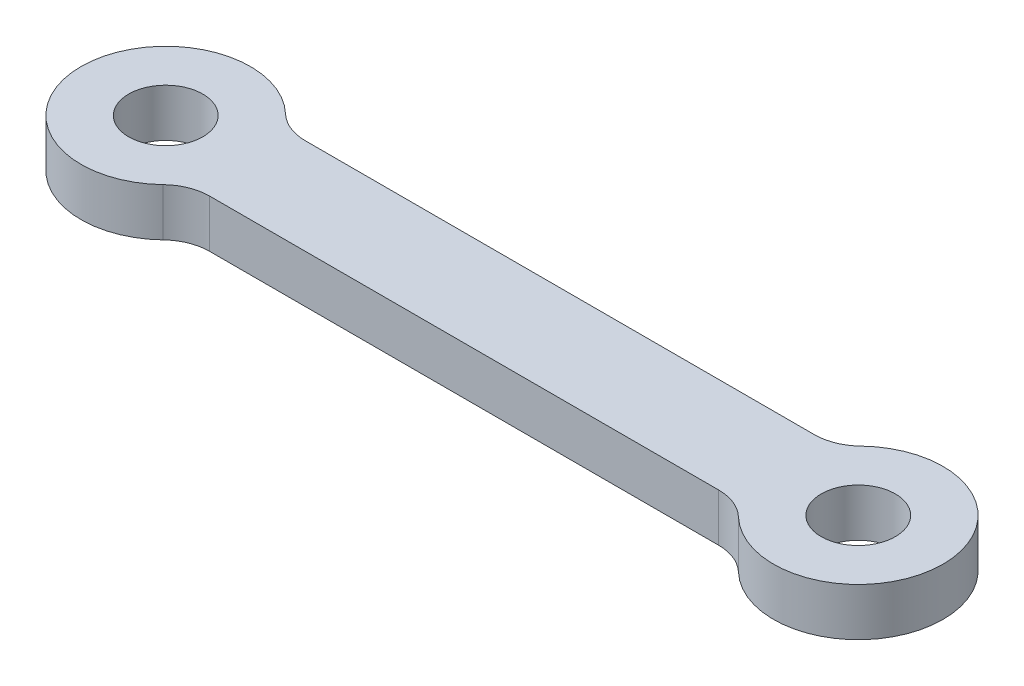
SolidWorks part; units mm, degrees
ref_plane "前视基准面" through (0, 0, 0) normal (0, 0, 1) x (1, 0, 0)
ref_plane "上视基准面" through (0, 0, 0) normal (0, 1, 0) x (1, 0, 0)
ref_plane "右视基准面" through (0, 0, 0) normal (1, 0, 0) x (0, 0, -1)
other "Configuration Table"
sketch "草图1" plane through (0, 0, 0) normal (0, 1, 0) x (1, 0, 0)
  line L0 (0, 0) -> (144.6352, 0) construction
  line L1 (14.6063, 10) -> (130.0289, 10)
  line L2 (14.6063, -10) -> (130.0289, -10)
  circle A0 centre (0, 0) radius 7.7444
  circle A1 centre (0, 0) radius 17.7015
  circle A2 centre (144.6352, 0) radius 7.7444
  circle A3 centre (144.6352, 0) radius 17.7015
  dimension "D1" = 20
extrude "凸台-拉伸1" add sketch "草图1" along normal blind 10
fillet "圆角1" radius 10 4 edges at (130.0289, 5, -10) (14.6063, 5, -10) (130.0289, 5, 10) (14.6063, 5, 10)
